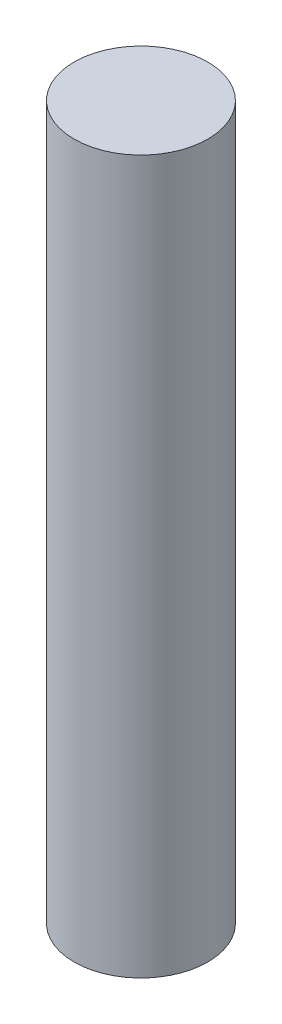
SolidWorks part; units mm, degrees
ref_plane "Front Plane" through (0, 0, 0) normal (0, 0, 1) x (1, 0, 0)
ref_plane "Top Plane" through (0, 0, 0) normal (0, 1, 0) x (1, 0, 0)
ref_plane "Right Plane" through (0, 0, 0) normal (1, 0, 0) x (0, 0, -1)
sketch "Sketch1" plane through (0, 0, 0) normal (0, 1, 0) x (1, 0, 0)
  circle A0 centre (0, 0) radius 3
  dimension "D1" = 6
extrude "Boss-Extrude1" add sketch "Sketch1" along normal blind 32
